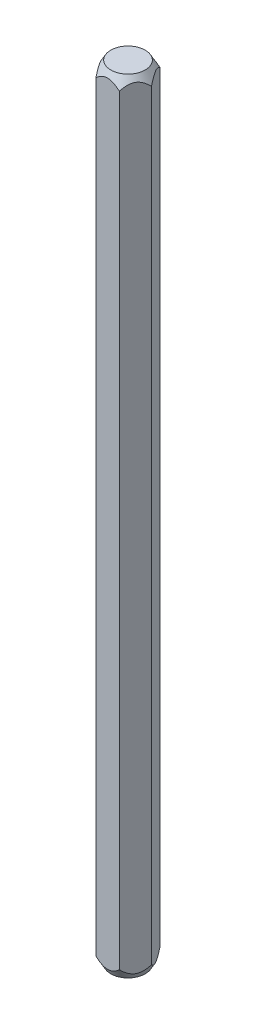
SolidWorks part; units mm, degrees
ref_plane "Front Plane" through (0, 0, 0) normal (0, 0, 1) x (1, 0, 0)
ref_plane "Top Plane" through (0, 0, 0) normal (0, 1, 0) x (1, 0, 0)
ref_plane "Right Plane" through (0, 0, 0) normal (1, 0, 0) x (0, 0, -1)
sketch "Sketch1" plane through (0, 0, 0) normal (0, 1, 0) x (1, 0, 0)
  line L0 (0, 0) -> (1.5, 0) construction
  line L7 (1.5, 0) -> (0.75, 1.299)
  line L8 (0.75, 1.299) -> (-0.75, 1.299)
  line L9 (-0.75, 1.299) -> (-1.5, 0)
  line L10 (-1.5, 0) -> (-0.75, -1.299)
  line L11 (-0.75, -1.299) -> (0.75, -1.299)
  line L12 (0.75, -1.299) -> (1.5, 0)
  circle A0 centre (0, 0) radius 1.5 construction
  dimension "D1" = 3
extrude "Boss-Extrude1" add sketch "Sketch1" along normal mid plane 50
sketch3d "3DSketch1"
  line L0 (0, -25, 0) -> (0, 25, 0)
  line L1 (1.5, 25, 0) -> (-1.5, 25, 0) construction
  line L2 (1.5, -25, 0) -> (-1.5, -25, 0) construction
  point P13 (0, -25, 0)
  point P14 (0, 25, 0)
sketch "Sketch2" plane through (0, 0, 0) normal (0, 0, 1) x (1, 0, 0)
  line L0 (1.5, 25) -> (1.5, 24.3)
  line L1 (1.5, 25) -> (1.5, -25) construction
  line L2 (1.5, 24.3) -> (1.1, 25)
  line L3 (1.1, 25) -> (1.5, 25)
  line L4 (1.5, -25) -> (1.5, -24.3)
  line L5 (1.5, -24.3) -> (1.1, -25)
  line L6 (1.1, -25) -> (1.5, -25)
  dimension "D1" = 0.7
  dimension "D2" = 0.4
revolve "Cut-Revolve1" cut sketch "Sketch2" angle 360 about L0
